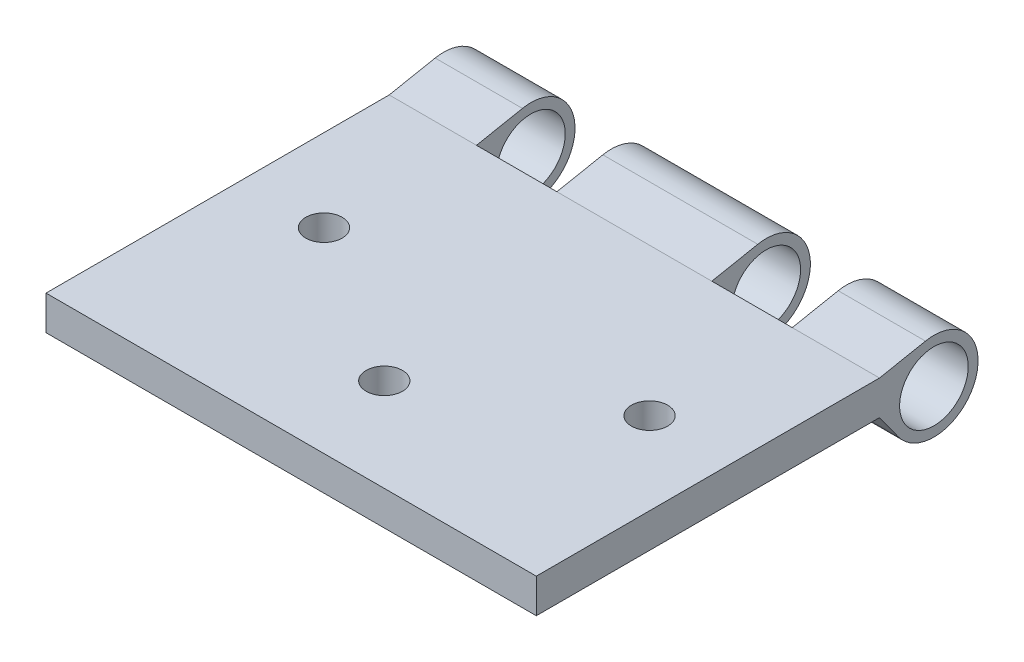
SolidWorks part; units mm, degrees
ref_plane "Front Plane" through (0, 0, 0) normal (0, 0, 1) x (1, 0, 0)
ref_plane "Top Plane" through (0, 0, 0) normal (0, 1, 0) x (1, 0, 0)
ref_plane "Right Plane" through (0, 0, 0) normal (1, 0, 0) x (0, 0, -1)
sketch "Sketch1" plane through (0, 0, 0) normal (0, 1, 0) x (1, 0, 0)
  line L0 (0, 17.5) -> (0, -17.5) construction
  line L1 (-25, 17.5) -> (25, 17.5)
  line L2 (-25, 17.5) -> (-25, -17.5)
  line L3 (-25, -17.5) -> (25, -17.5)
  line L4 (25, 17.5) -> (25, -17.5)
  line L5 (0, 0) -> (0, -17.5) construction
  line L7 (-25, 0) -> (25, 0) construction
  point P0 (0, 0)
  point P11 (0, 0)
  point P12 (0.699, -16.7787)
  point P13 (0, 0)
  point P14 (0, 0)
  point P15 (0, 0)
  point P16 (0.7044, -17.5902)
  dimension "D1" = 35
  dimension "D2" = 50
extrude "Boss-Extrude1" add sketch "Sketch1" along normal blind 3.5
sketch "Sketch2" plane through (0, 3.5, 0) normal (0, 1, 0) x (1, 0, 0)
  line L0 (0, 0) -> (0, 17.5) construction
  line L1 (25, 17.5) -> (-25, 17.5) construction
  line L2 (-25, 17.5) -> (-25, -17.5) construction
  line L3 (25, -17.5) -> (25, 17.5) construction
  circle A0 centre (0, -8) radius 1.85
  circle A1 centre (16.6, 2.45) radius 1.85
  circle A2 centre (-16.6, 2.45) radius 1.85
  point P15 (0, 0)
  point P16 (0, 0)
  point P17 (0.9757, -0.2365)
  dimension "D1" = 3.7
  dimension "D2" = 3.7
  dimension "D3" = 3.7
  dimension "D4" = 8.4
  dimension "D5" = 8.4
  dimension "D6" = 2.45
  dimension "D7" = 8
  dimension "D8" = 2.45
extrude "Cut-Extrude1" cut sketch "Sketch2" against normal through all
sketch "Sketch3" plane through (0, 0, 0) normal (1, 0, 0) x (0, 0, -1)
  line L0 (17.5, 3.5) -> (17.5, 0) construction
  line L1 (17.5, 0) -> (19.4014, -2.6339)
  line L2 (17.5, 1.6553) -> (17.5, 3.5)
  line L3 (17.5, 3.5) -> (22.1864, 4.4164)
  line L4 (17.5, 1.6553) -> (17.5, 0)
  line L6 (17.5, 0) -> (23.05, 0) construction
  arc A0 (19.4014, -2.6339) -> (22.1864, 4.4164) centre (23.05, 0) ccw
  circle A1 centre (23.05, 0) radius 3.5
  dimension "D1" = 7
  dimension "D3" = 4.5
  dimension "D2" = 5.55
extrude "Boss-Extrude2" add sketch "Sketch3" along normal mid plane 50
ref_plane "Plane1" through (7.9, 0, 0) normal (1, 0, 0) x (0, 0, -1)
sketch "Sketch4" plane through (7.9, 0, 0) normal (1, 0, 0) x (0, 0, -1)
  line L0 (17.5, 3.5) -> (17.5, 0)
  line L1 (-17.5, 3.5) -> (17.5, 3.5) construction
  line L2 (17.5, 0) -> (19.4014, -2.6339)
  line L3 (17.5, 3.5) -> (22.1864, 4.4164)
  arc A0 (19.4014, -2.6339) -> (22.1864, 4.4164) centre (23.05, 0) ccw
extrude "Cut-Extrude2" cut sketch "Sketch4" along normal blind 8.2
mirror "Mirror1" about plane through (0, 0, 0) normal (1, 0, 0) of "Cut-Extrude2"
